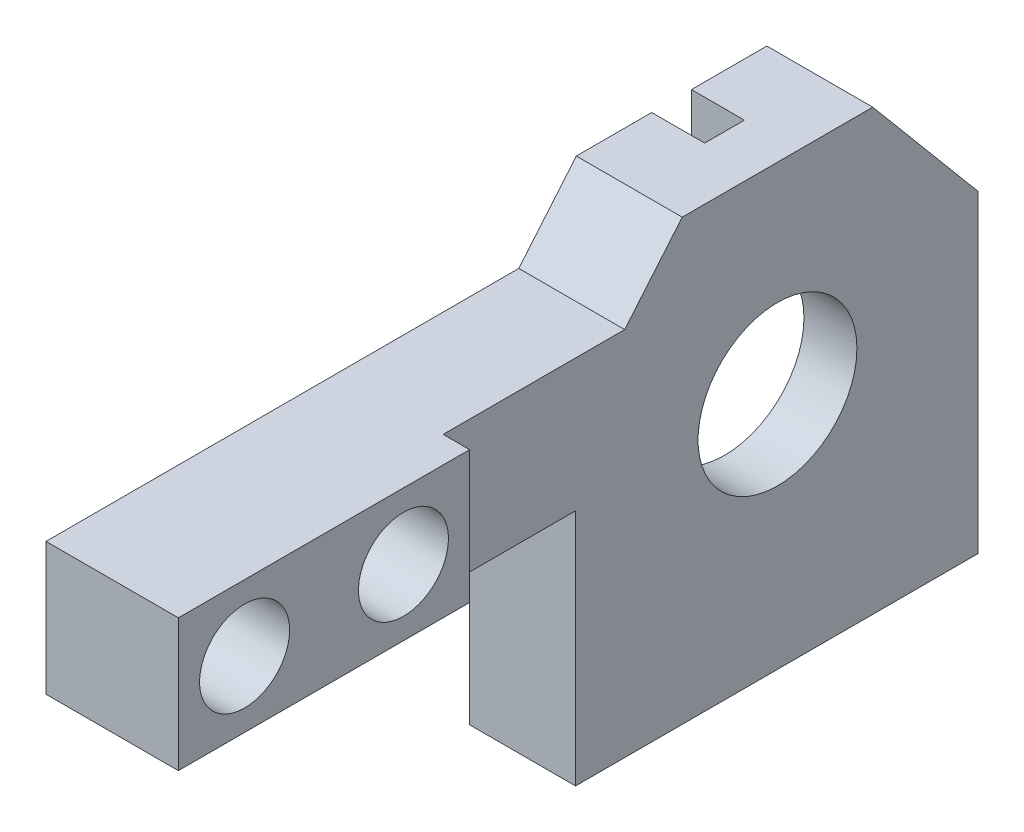
SolidWorks part; units mm, degrees
ref_plane "Front Plane" through (0, 0, 0) normal (0, 0, 1) x (1, 0, 0)
ref_plane "Top Plane" through (0, 0, 0) normal (0, 1, 0) x (1, 0, 0)
ref_plane "Right Plane" through (0, 0, 0) normal (1, 0, 0) x (0, 0, -1)
sketch "Sketch1" plane through (0, 0, 0) normal (1, 0, 0) x (0, 0, -1)
  line L0 (-6.1093, 3.9687) -> (-3.1473, 7.4987)
  line L1 (-3.1473, 7.4987) -> (-1.2321, 7.4987)
  line L2 (-6.1093, 3.9687) -> (-6.1093, -5.0913)
  line L3 (-6.1093, -5.0913) -> (-3.9821, -5.0913)
  line L4 (5.0907, 4.0335) -> (5.0907, -5.0913)
  line L5 (-4.0799, 9.4987) -> (-1.2321, 9.4987)
  line L6 (-8.1093, 4.6966) -> (-8.1093, -7.0913)
  line L7 (-8.1093, -7.0913) -> (-3.9821, -7.0913)
  line L8 (7.0907, 4.7614) -> (7.0907, -7.0913)
  line L9 (5.0907, 4.0335) -> (2.1831, 7.4987)
  line L10 (-8.1093, 4.6966) -> (-4.0799, 9.4987)
  line L11 (3.1157, 9.4987) -> (7.0907, 4.7614)
  line L12 (0.2679, 7.4987) -> (0.2679, 9.4987)
  line L13 (-1.2321, 7.4987) -> (-1.2321, 9.4987)
  line L14 (3.0179, -5.0913) -> (3.0179, -7.0913)
  line L15 (-3.9821, -5.0913) -> (-3.9821, -7.0913)
  line L16 (-0.4821, 1.9087) -> (-0.4821, -6.5913) construction
  line L17 (-8.1093, 1.9087) -> (7.0907, 1.9087) construction
  line L18 (0.2679, 9.4987) -> (3.1157, 9.4987)
  line L19 (0.2679, 7.4987) -> (2.1831, 7.4987)
  line L20 (3.0179, -5.0913) -> (5.0907, -5.0913)
  line L21 (3.0179, -7.0913) -> (7.0907, -7.0913)
  point P20 (1.2255, 7.4987)
  dimension "D1" = 2
  dimension "D2" = 2
  dimension "D3" = 2
  dimension "D4" = 2
  dimension "D5" = 2
  dimension "D6" = 2
  dimension "D7" = 40
  dimension "D8" = 40
  dimension "D9" = 3.53
  dimension "D10" = 3.5
  dimension "D11" = 7
  dimension "D12" = 3.5
  dimension "D13" = 0.75
  dimension "D14" = 0.75
  dimension "D15" = 5.59
  dimension "D16" = 11.2
sketch "Sketch2" plane through (0, 0, 0) normal (1, 0, 0) x (0, 0, -1)
  line L0 (-8.1093, -7.0913) -> (-8.1093, 4.6966)
  line L1 (-8.1093, 4.6966) -> (-4.0799, 9.4987)
  line L2 (-4.0799, 9.4987) -> (3.1157, 9.4987)
  line L3 (3.1157, 9.4987) -> (7.0907, 4.7614)
  line L4 (7.0907, 4.7614) -> (7.0907, -7.0913)
  line L5 (7.0907, -7.0913) -> (-8.1093, -7.0913)
extrude "Boss-Extrude1" add sketch "Sketch2" against normal blind 2
extrude "Boss-Extrude2" add sketch "Sketch1" along normal blind 2
sketch "Sketch3" plane through (0, 0, 0) normal (1, 0, 0) x (0, 0, -1)
  circle A0 centre (-0.4821, 1.9087) radius 3
extrude "Cut-Extrude1" cut sketch "Sketch3" against normal blind 2
sketch "Sketch4" plane through (2, 0, 0) normal (1, 0, 0) x (0, 0, -1)
  line L0 (-15.4821, 1.9087) -> (-8.1093, 1.9087)
  line L7 (-6.2532, 6.9087) -> (-20.486, 6.9087)
  line L19 (-8.1093, 4.6966) -> (-8.1093, 1.9087)
  line L20 (-8.1093, 4.6966) -> (-6.2532, 6.9087)
  line L21 (-4.0799, 9.4987) -> (-8.1093, 4.6966) construction
  line L22 (-15.4821, 1.9087) -> (-24.1093, 1.9087)
  line L23 (-24.1093, 1.9087) -> (-24.1093, 6.9087)
  line L24 (-24.1093, 6.9087) -> (-20.486, 6.9087)
  circle A0 centre (-15.6093, 4.4087) radius 1.7
  circle A2 centre (-21.6093, 4.4087) radius 1.7
  dimension "D7" = 3.4
  dimension "D6" = 3.4
  dimension "D1" = 5
  dimension "D3" = 2.5
  dimension "D4" = 2.5
  dimension "D5" = 6
extrude "Boss-Extrude3" add sketch "Sketch4" against normal blind 5
sketch "Sketch5" plane through (-3, 0, 0) normal (-1, 0, 0) x (0, 0, 1)
  line L7 (6.2532, 6.9087) -> (24.1093, 6.9087) construction
  line L8 (8.1093, 6.9087) -> (6.2532, 6.9087)
  line L9 (6.2532, 6.9087) -> (8.1093, 4.6966)
  line L10 (8.1093, 6.9087) -> (13.1093, 6.9087)
  line L11 (13.1093, 6.9087) -> (13.1093, 1.9087)
  line L12 (24.1093, 1.9087) -> (8.1093, 1.9087) construction
  line L13 (13.1093, 1.9087) -> (8.1093, 1.9087)
  line L14 (8.1093, 1.9087) -> (8.1093, 4.6966)
  circle A0 centre (15.6093, 4.4087) radius 1.7 construction
  dimension "D1" = 2.5
extrude "Cut-Extrude2" cut sketch "Sketch5" against normal blind 1
mirror "Mirror1" about plane through (0, 0, 0) normal (1, 0, 0) of bodies 105
delete or keep bodies "Body-Delete/Keep 1" type delete bodies bodies 105
